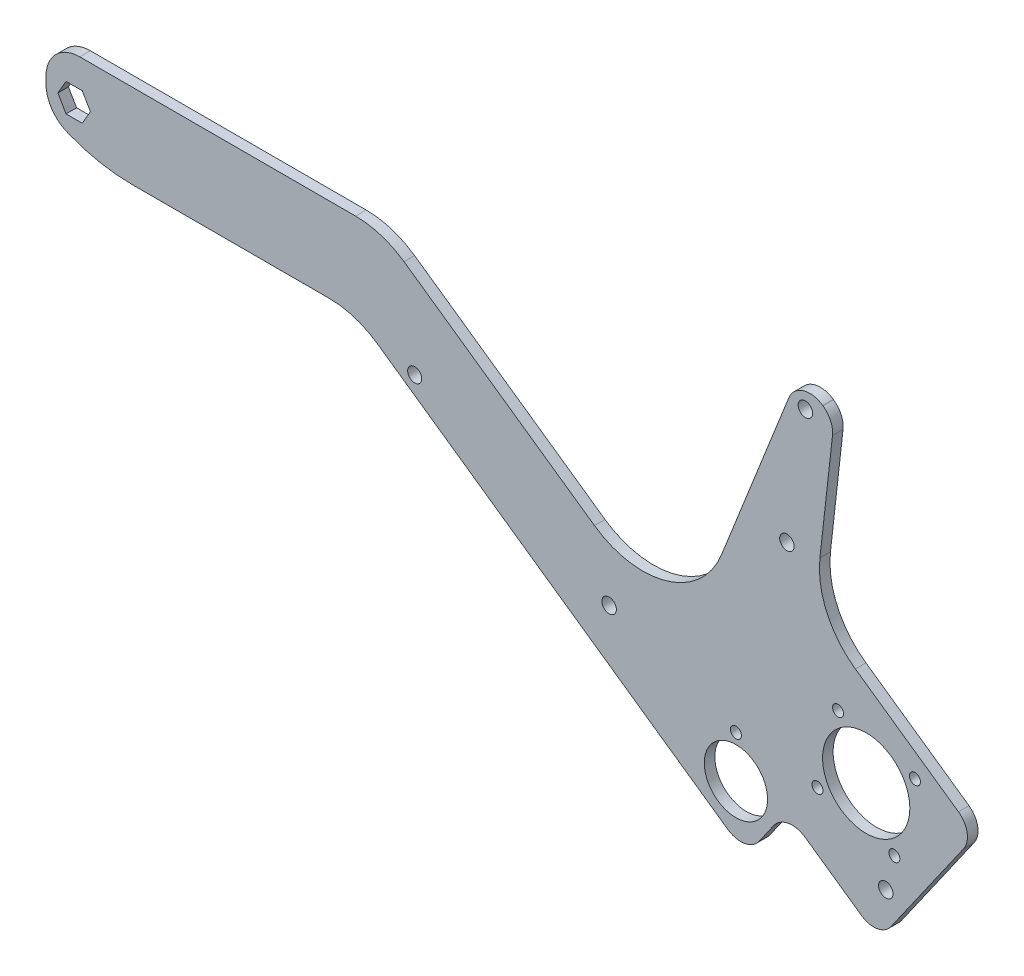
SolidWorks part; units mm, degrees
material "6061 Alloy"
ref_plane "Front Plane" through (0, 0, 0) normal (0, 0, 1) x (1, 0, 0)
ref_plane "Top Plane" through (0, 0, 0) normal (0, 1, 0) x (1, 0, 0)
ref_plane "Right Plane" through (0, 0, 0) normal (1, 0, 0) x (0, 0, -1)
sketch "Sketch1" plane through (0, 0, 0) normal (0, 0, 1) x (1, 0, 0)
  line L3 (27.94, 38.1) -> (164.4129, 38.1)
  line L5 (18.0677, 19.05) -> (21.7338, 12.7)
  line L6 (21.7338, 12.7) -> (29.0662, 12.7)
  line L7 (29.0662, 12.7) -> (32.7323, 19.05)
  line L8 (32.7323, 19.05) -> (29.0662, 25.4)
  line L9 (29.0662, 25.4) -> (21.7338, 25.4)
  line L10 (21.7338, 25.4) -> (18.0677, 19.05)
  line L15 (152.4, 0) -> (328.6833, -123.4349)
  line L18 (339.1081, 24.304) -> (370.3178, 2.4507) construction
  line L19 (328.6833, -123.4349) -> (346.8943, -97.4268)
  line L21 (299.6549, -56.5975) -> (164.4129, 38.1)
  line L24 (347.013, 7.9162) -> (352.1121, 15.1984) construction
  line L26 (12.7, 22.86) -> (12.7, 19.9526)
  line L27 (152.4, 0) -> (51.4951, 0)
  line L28 (23.8917, 5.1754) -> (22.4193, 5.7476)
  line L32 (359.3911, -13.1541) -> (424.4113, -58.6818)
  line L33 (347.013, 7.9162) -> (376.1507, 49.5291) construction
  line L34 (376.1507, 49.5291) -> (355.3442, 64.098) construction
  line L35 (299.6549, -56.5975) -> (352.6409, 76.8435)
  line L36 (352.6409, 76.8435) -> (368.2458, 65.9169)
  line L38 (368.2458, 65.9169) -> (399.4554, 44.0636) construction
  line L39 (399.4554, 44.0636) -> (370.3178, 2.4507) construction
  line L40 (368.2458, 65.9169) -> (359.3911, -13.1541)
  line L42 (152.4, 0) -> (174.2533, 31.2097) construction
  line L43 (346.8943, -97.4268) -> (380.7048, -121.1012)
  line L44 (393.9705, -118.762) -> (426.7504, -71.9475)
  line L45 (324.005, -96.9034) -> (324.005, -77.8534) construction
  line L46 (386.1681, -113.2987) -> (418.948, -66.4842) construction
  line L47 (324.005, -96.9034) -> (266.7873, -56.8391) construction
  circle A0 centre (25.4, 19.05) radius 6.35 construction
  circle A1 centre (324.005, -96.9034) radius 14.2875
  circle A10 centre (347.013, 7.9162) radius 3.2639
  arc A11 (51.4951, 0) -> (23.8917, 5.1754) centre (51.4951, 76.2) cw
  arc A12 (22.4193, 5.7476) -> (12.7, 19.9526) centre (27.94, 19.9526) cw
  arc A13 (27.94, 38.1) -> (12.7, 22.86) centre (27.94, 22.86) ccw
  circle A14 centre (324.005, -77.8534) radius 2.4892
  circle A20 centre (355.3442, 64.098) radius 3.2639
  arc A21 (424.4113, -58.6818) -> (426.7504, -71.9475) centre (418.948, -66.4842) cw
  arc A22 (380.7048, -121.1012) -> (393.9705, -118.762) centre (386.1681, -113.2987) ccw
  circle A23 centre (391.6314, -105.4963) radius 3.2639
  circle A24 centre (266.7873, -56.8391) radius 3.2639
  point P28 (0, 0)
  point P29 (12.7, 9.525)
  point P32 (12.7, 38.1)
  point P42 (328.6833, -123.4349)
  point P47 (432.2138, -64.1451)
  point P49 (427.5139, -192.6369)
  point P51 (388.5072, -126.5645)
  point P52 (0, 0)
  point P53 (392.434, -104.3502)
  dimension "D2" = 12.7
  dimension "D4" = 28.575
  dimension "D9" = 196.1521
  dimension "D11" = 19.05
  dimension "D12" = 38.1
  dimension "D14" = 76.2
  dimension "D16" = 38.1
  dimension "D17" = 50.8
  dimension "D20" = 31.75
  dimension "D22" = 6.5278
  dimension "D26" = 15.24
  dimension "D28" = 4.9784
  dimension "D30" = 9.525
  dimension "D31" = 18.1474
  dimension "D32" = 6.5278
  dimension "D33" = 50.8
  dimension "D35" = 6.5278
  dimension "D39" = 6.5278
  dimension "D27" = 76.2
  dimension "D40" = 69.85
  dimension "D3" = 25.4
  dimension "D5" = 127
  dimension "D6" = 38.1
  dimension "D7" = 215
  dimension "D8" = 165.1
  dimension "D10" = 152.4
  dimension "D13" = 28.575
  dimension "D15" = 19.05
  dimension "D18" = 38.1
  dimension "D19" = 19.05
  dimension "D21" = 8.89
  dimension "D23" = 15.875
  dimension "D24" = 19.05
  dimension "D25" = 12.7
  dimension "D29" = 88.9
  dimension "D34" = 25.4
  dimension "D36" = 38.1
  dimension "D37" = 177.8
  dimension "D38" = 19.05
  dimension "D41" = 19.05
extrude "Boss-Extrude1" add sketch "Sketch1" along normal blind 4.7625
sketch "Sketch2" plane through (0, 0, 4.7625) normal (0, 0, 1) x (1, 0, 0)
  line L0 (382.793, -68.2999) -> (339.0865, -130.7193) construction
  line L1 (152.4, 0) -> (328.6833, -123.4349) construction
  line L2 (152.4, 0) -> (328.6833, -123.4349) construction
  line L4 (370.093, -46.3029) -> (395.493, -90.2969) construction
  line L5 (152.4, 0) -> (328.6833, -123.4349) construction
  line L7 (179.07, -10.5987) -> (332.4776, -118.0159) construction
  line L9 (328.6833, -123.4349) -> (346.8943, -97.4268) construction
  circle A0 centre (382.793, -68.2999) radius 25.4 construction
  circle A2 centre (382.793, -68.2999) radius 19.685
  circle A3 centre (395.493, -90.2969) radius 2.4892
  circle A6 centre (360.796, -80.9999) radius 2.4892
  circle A7 centre (370.093, -46.3029) radius 2.4892
  circle A9 centre (404.7901, -55.5999) radius 2.4892
  circle A10 centre (179.07, -10.5987) radius 3.175
  point P17 (382.793, -68.2999)
  point P18 (382.793, -68.2999)
  point P27 (164.4129, 38.1)
  dimension "D1" = 50.8
  dimension "D2" = 4
  dimension "D3" = 39.37
  dimension "D4" = 4.9784
  dimension "D7" = 6.35
  dimension "D11" = 218.3801
  dimension "D6" = 76.2
  dimension "D8" = 179.07
  dimension "D9" = 6.6153
  dimension "D10" = 25
extrude "Cut-Extrude1" cut sketch "Sketch2" against normal through all both and the other way through all
fillet "Fillet3" radius 38.1 4 edges at (152.4, 0, 2.3813) (164.4129, 38.1, 2.3813) (299.6549, -56.5975, 2.3813) (359.3911, -13.1541, 2.3813)
fillet "Fillet4" radius 10.16 4 edges at (352.6409, 76.8435, 2.3813) (368.2458, 65.9169, 2.3813) (328.6833, -123.4349, 2.3813) (346.8943, -97.4268, 2.3813)
